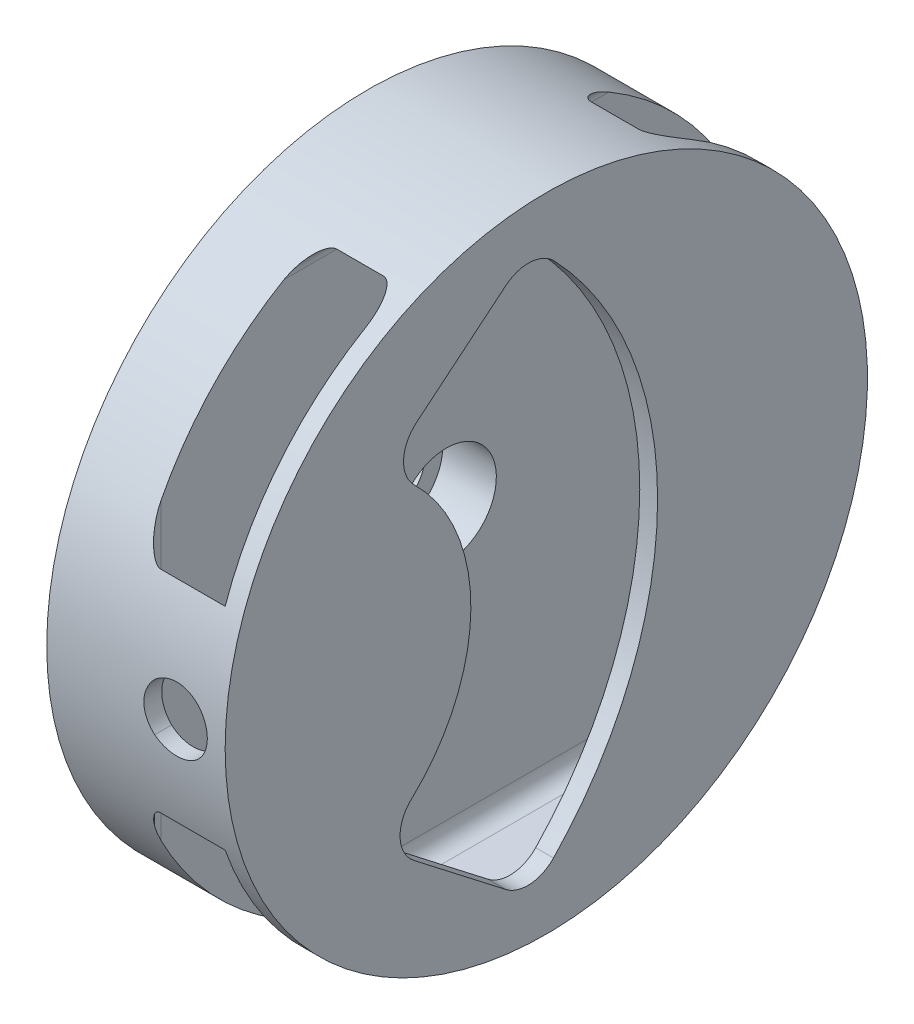
SolidWorks part; units mm, degrees
ref_plane "Alzado" through (0, 0, 0) normal (0, 0, 1) x (1, 0, 0)
ref_plane "Planta" through (0, 0, 0) normal (0, 1, 0) x (1, 0, 0)
ref_plane "Vista lateral" through (0, 0, 0) normal (1, 0, 0) x (0, 0, -1)
sketch "Croquis1" plane through (0, 0, 0) normal (0, 0, 1) x (1, 0, 0)
  line L0 (-25.3649, 0) -> (29.1754, 0) construction
  line L1 (0, 0) -> (0, 3)
  line L2 (0, 3) -> (10, 3)
  line L3 (10, 3) -> (10, 18)
  line L4 (10, 18) -> (20, 18)
  line L5 (20, 18) -> (20, 0)
  line L6 (20, 0) -> (0, 0)
  dimension "D1" = 10
  dimension "D2" = 10
  dimension "D3" = 18
  dimension "D4" = 3
revolve "Revolución1" add sketch "Croquis1" angle 360 about L0
sketch "Croquis2" plane through (20, 0, 0) normal (1, 0, 0) x (0, 0, -1)
  line L0 (-0.9028, 17.9773) -> (-0.9028, -17.9773) construction
  line L1 (-18, 0) -> (18, 0) construction
  line L2 (-9.1834, 8.9025) -> (-0.9028, 15.75)
  line L3 (-9.5062, -9.0946) -> (-0.9028, -15.75)
  line L4 (-7.1886, 15.75) -> (6.2956, 15.75) construction
  line L5 (-5.7152, -15.75) -> (7.7244, -15.75) construction
  line L6 (11, 0) -> (-11, 0) construction
  circle A0 centre (0, 0) radius 18 construction
  arc A1 (-0.9028, 15.75) -> (-0.9028, -15.75) centre (-14.702, 0) cw
  arc A2 (-9.1834, 8.9025) -> (-9.5062, -9.0946) centre (-14.702, 0) cw
  point P14 (6.238, 0)
  dimension "D2" = 18
  dimension "D3" = 10.4742
  dimension "D4" = 20.9399
  dimension "D1" = 31.5
  dimension "D5" = 10.8772
extrude "Cortar-Extruir1" cut sketch "Croquis2" against normal blind 1
ref_plane "Plano1" through (0, 0, -18) normal (0, 0, -1) x (-1, 0, 0)
sketch "Croquis4" plane through (0, 0, -18) normal (0, 0, -1) x (-1, 0, 0)
  line L4 (-19, 8.9025) -> (-19, -9.0946) construction
  line L5 (-19, 8.9025) -> (-19, -9.0946)
  line L6 (-19, 15.75) -> (-20, 15.75) construction
  line L7 (-19, -15.75) -> (-20, -15.75) construction
  line L8 (-19, 15.75) -> (-20, 15.75)
  line L9 (-19, -15.75) -> (-20, -15.75)
  line L10 (-19, -16.2748) -> (-14.4, -16.2748)
  line L11 (-14.4, -16.2748) -> (-14.4, 16.5242)
  line L12 (-14.4, 16.5242) -> (-19, 16.5242)
  line L13 (-19, 16.5242) -> (-19, -16.2748)
  dimension "D1" = 4.6
extrude "Cortar-Extruir3" cut sketch "Croquis4" against normal blind 35 contours L12 L13 L5 L10 L11
ref_plane "Plano2" through (0, 0, 18) normal (0, 0, 1) x (1, 0, 0)
sketch "Croquis5" plane through (0, 0, 18) normal (0, 0, 1) x (1, 0, 0)
  line L0 (11, 0) -> (-11, 0) construction
  line L1 (14.4, -5.9161) -> (14.4, 5.9161) construction
  line L2 (14.4, -5.9161) -> (14.4, 5.9161)
  line L3 (19, 5.9161) -> (19, -5.9161) construction
  line L4 (19, 5.9161) -> (19, -5.9161)
  arc A0 (16, -1.3416) -> (16, 1.3416) centre (17.2, 0) ccw
  arc A1 (16, -1.3416) -> (16, 1.3416) centre (17.3416, 0) cw
  dimension "D1" = 3.6
extrude "Cortar-Extruir4" cut sketch "Croquis5" against normal blind 24 contours A0 L2
sketch "Croquis6" plane through (0, 0, 0) normal (-1, 0, 0) x (0, 0, 1)
  circle A0 centre (0, 0) radius 1.8
  dimension "D1" = 3.6
extrude "Cortar-Extruir5" cut sketch "Croquis6" against normal up to next
sketch "Croquis7" plane through (14.4, 0, 0) normal (1, 0, 0) x (0, 0, -1)
  circle A0 centre (0, 0) radius 2.8
  dimension "D1" = 5.6
extrude "Cortar-Extruir6" cut sketch "Croquis7" against normal blind 3 and the other way through all
fillet "Redondeo1" radius 2 4 edges at (19.5, -15.75, 0.9028) (19.5, -9.0946, 9.5062) (19.5, 15.75, 0.9028) (19.5, 8.9025, 9.1834)
fillet "Redondeo2" radius 1 4 edges at (14.4, 16.5242, 0) (14.4, -16.2748, 0) (19, -16.2748, 0) (19, 16.5242, 0)
fillet "Redondeo3" radius 1 1 edges at (14.4, 0, 17)
